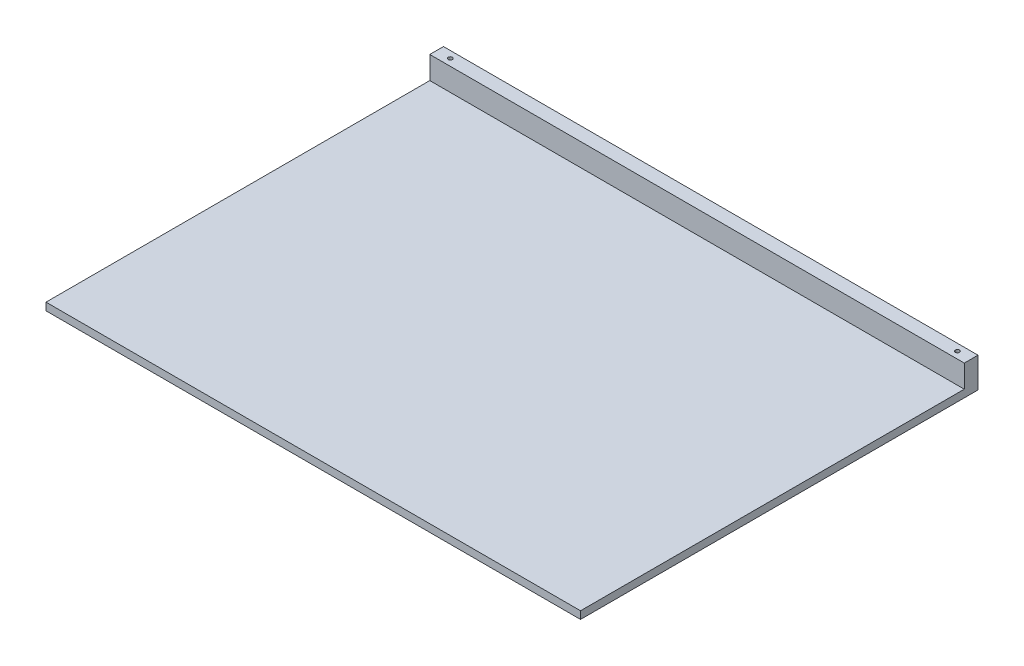
SolidWorks part; units mm, degrees
ref_plane "Alzado" through (0, 0, 0) normal (0, 0, 1) x (1, 0, 0)
ref_plane "Planta" through (0, 0, 0) normal (0, 1, 0) x (1, 0, 0)
ref_plane "Vista lateral" through (0, 0, 0) normal (1, 0, 0) x (0, 0, -1)
sketch "Croquis2" plane through (0, 0, 0) normal (0, 1, 0) x (1, 0, 0)
  line L1 (195, 145) -> (-195, 145)
  line L2 (195, 145) -> (195, -145)
  line L3 (195, -145) -> (-195, -145)
  line L4 (-195, 145) -> (-195, -145)
  line L5 (195, 145) -> (-195, -145) construction
  line L6 (195, -145) -> (-195, 145) construction
  point P0 (0, 0)
extrude "Saliente-Extruir2" add sketch "Croquis2" along normal blind 10
sketch "Croquis3" plane through (0, 10, 0) normal (0, 1, 0) x (1, 0, 0)
  line L0 (195, -145) -> (195, 145) construction
  line L1 (-195, -145) -> (195, -145)
  line L2 (-195, -145) -> (-195, -138)
  line L3 (-195, -138) -> (195, -138)
  line L4 (195, -145) -> (195, -138)
extrude "Saliente-Extruir3" add sketch "Croquis3" along normal blind 25
sketch "Croquis5" plane through (-195, 0, 0) normal (-1, 0, 0) x (0, 0, 1)
  line L0 (145, 0) -> (51.1207, -135.6896)
  line L2 (51.1207, -135.6896) -> (-145, 0)
  line L3 (-145, 0) -> (145, 0)
  dimension "D1" = 165
  dimension "D2" = 90
extrude "Saliente-Extruir4" add sketch "Croquis5" against normal blind 390
sketch "Croquis6" plane through (-195, 0, 0) normal (-1, 0, 0) x (0, 0, 1)
  line L0 (-145, 0) -> (145, 0)
  line L1 (145, 0) -> (51.1207, -135.6896)
  line L2 (51.1207, -135.6896) -> (-145, 0)
extrude "Cortar-Extruir1" cut sketch "Croquis6" against normal blind 180
sketch "Croquis7" plane through (195, 0, 0) normal (1, 0, 0) x (0, 0, -1)
  line L0 (145, 0) -> (-145, 0)
  line L1 (-145, 0) -> (-51.1207, -135.6896)
  line L2 (-51.1207, -135.6896) -> (145, 0)
extrude "Cortar-Extruir2" cut sketch "Croquis7" against normal blind 180
sketch "Croquis8" plane through (0, -67.8448, -46.9397) normal (0, -0.8224, -0.569) x (-1, 0, 0)
  line L0 (15, -119.2424) -> (105, 119.2424)
  line L1 (15, 119.2424) -> (195, 119.2424) construction
  line L2 (105, 119.2424) -> (75, 119.2424)
  line L3 (75, 119.2424) -> (15, -39.7475)
  line L4 (15, 119.2424) -> (15, -119.2424) construction
  line L5 (15, -39.7475) -> (15, -119.2424)
extrude "Saliente-Extruir5" add sketch "Croquis8" against normal blind 179
sketch "Croquis10" plane through (-195, 0, 0) normal (-1, 0, 0) x (0, 0, 1)
  line L0 (138, 35) -> (138, 10) construction
  line L1 (-145, 10) -> (138, 10)
  line L2 (-145, 10) -> (-145, 204.11)
  line L3 (-145, 204.11) -> (138, 204.11)
  line L4 (138, 10) -> (138, 204.11)
  dimension "D1" = 0
extrude "Cortar-Extruir5" cut sketch "Croquis10" against normal blind 236
sketch "Croquis11" plane through (-195, 0, 0) normal (-1, 0, 0) x (0, 0, 1)
  line L0 (145, 17.0241) -> (145, 0)
  line L1 (145, 0) -> (165.7896, 1.6032)
  line L2 (165.7896, 1.6032) -> (161.3582, 19.3089)
  line L3 (161.3582, 19.3089) -> (145, 17.0241)
extrude "Cortar-Extruir6" cut sketch "Croquis11" against normal blind 236
sketch "Croquis12" plane through (0, -67.8448, -46.9397) normal (0, -0.8224, -0.569) x (-1, 0, 0)
  line L0 (-15, -119.2424) -> (-105, 119.2424)
  line L1 (-195, 119.2424) -> (-15, 119.2424) construction
  line L2 (-105, 119.2424) -> (-75, 119.2424)
  line L3 (-75, 119.2424) -> (-15, -39.7475)
  line L4 (-15, -119.2424) -> (-15, 119.2424) construction
  line L5 (-15, -39.7475) -> (-15, -119.2424)
extrude "Saliente-Extruir6" add sketch "Croquis12" against normal blind 236
sketch "Croquis13" plane through (195, 0, 0) normal (1, 0, 0) x (0, 0, -1)
  line L1 (-138, 10) -> (201.7989, 10)
  line L2 (-138, 10) -> (-138, 246.8197)
  line L3 (-138, 246.8197) -> (201.7989, 246.8197)
  line L4 (201.7989, 10) -> (201.7989, 246.8197)
  line L5 (-145, 0) -> (-189.7765, 0)
  line L6 (-145, 0) -> (-145, 75.1047)
  line L7 (-145, 75.1047) -> (-189.7765, 75.1047)
  line L8 (-189.7765, 0) -> (-189.7765, 75.1047)
extrude "Cortar-Extruir7" cut sketch "Croquis13" against normal blind 500
sketch "Croquis14" plane through (195, 0, 0) normal (1, 0, 0) x (0, 0, -1)
  line L1 (-138, 35) -> (-197.446, 35)
  line L2 (-138, 35) -> (-138, 116.4359)
  line L3 (-138, 116.4359) -> (-197.446, 116.4359)
  line L4 (-197.446, 35) -> (-197.446, 116.4359)
extrude "Cortar-Extruir8" cut sketch "Croquis14" against normal blind 500
sketch "Croquis15" plane through (-195, 0, 0) normal (-1, 0, 0) x (0, 0, 1)
  line L0 (-145, 0) -> (145, 0) construction
  line L1 (-127, 0) -> (-77, 0)
  line L2 (-127, 0) -> (-127, -5)
  line L3 (-127, -5) -> (-77, -5)
  line L4 (-77, 0) -> (-77, -5)
  line L6 (138, 35) -> (138, 10) construction
  dimension "D1" = 50
  dimension "D2" = 215
  dimension "D3" = 5
extrude "Cortar-Extruir9" cut sketch "Croquis15" against normal blind 500
sketch "Croquis16" plane through (0, 10, 0) normal (0, 1, 0) x (1, 0, 0)
  line L1 (-195, 145) -> (195, 145)
  line L2 (-195, 145) -> (-195, -138)
  line L3 (-195, -138) -> (195, -138)
  line L4 (195, 145) -> (195, -138)
extrude "Cortar-Extruir10" cut sketch "Croquis16" against normal blind 10
sketch "Croquis17" plane through (0, 0, 0) normal (0, 1, 0) x (1, 0, 0)
  line L0 (-99.4138, 127) -> (-99.4138, 145) construction
  line L1 (-105, 145) -> (-75, 145) construction
  line L2 (-75, 145) -> (-75, 127) construction
  line L3 (-69.4138, 127) -> (-99.4138, 127) construction
  line L5 (15, 145) -> (-15, 145) construction
  line L6 (75, 145) -> (105, 145) construction
  circle A0 centre (-87.205, 136) radius 3.75
  circle A1 centre (0, 136) radius 3.75
  circle A2 centre (87.205, 136) radius 3.75
  dimension "D1" = 9
  dimension "D2" = 7.5
  dimension "D7" = 7.5
  dimension "D8" = 7.5
  dimension "D3" = 9
  dimension "D4" = 12.205
  dimension "D5" = 12.205
  dimension "D6" = 9
extrude "Cortar-Extruir11" cut sketch "Croquis17" against normal blind 10
sketch "Croquis18" plane through (0, 0, 0) normal (0, 1, 0) x (1, 0, 0)
  circle A0 centre (-87.205, 136) radius 1.5
  circle A1 centre (-87.205, 136) radius 3.75
  circle A2 centre (0, 136) radius 3.75
  circle A3 centre (0, 136) radius 1.5
  circle A4 centre (87.205, 136) radius 1.5
  circle A5 centre (87.205, 136) radius 3.75
extrude "Saliente-Extruir8" add sketch "Croquis18" against normal blind 4
sketch "Croquis19" plane through (0, 0, 0) normal (0, 1, 0) x (1, 0, 0)
  line L0 (-15, -48.3333) -> (-53.8966, 77) construction
  line L1 (53.8966, 77) -> (15, -48.3333) construction
  line L2 (-17.1724, -138) -> (17.1724, -138) construction
  circle A0 centre (-52.5333, 22) radius 1.5
  circle A1 centre (0, 22) radius 1.5
  circle A2 centre (52.5333, 22) radius 1.5
  circle A3 centre (0, -58) radius 1.5
  circle A4 centre (0, -116) radius 1.5
  dimension "D1" = 15
  dimension "D2" = 15
  dimension "D6" = 80
  dimension "D7" = 3
  dimension "D3" = 160
  dimension "D4" = 0
  dimension "D5" = 0
  dimension "D8" = 22
extrude "Saliente-Extruir10" add sketch "Croquis19" along normal blind 15
sketch "Croquis20" plane through (0, 0, 0) normal (0, 1, 0) x (1, 0, 0)
  circle A0 centre (-87.205, 136) radius 1.5
  circle A1 centre (0, 136) radius 1.5
  circle A2 centre (87.205, 136) radius 1.5
extrude "Saliente-Extruir11" add sketch "Croquis20" along normal blind 15 separate body
sketch "Croquis21" plane through (0, 0, 0) normal (0, 1, 0) x (1, 0, 0)
  line L1 (-195, -138) -> (195, -138)
  line L2 (-195, -138) -> (-195, 145)
  line L3 (-195, 145) -> (195, 145)
  line L4 (195, -138) -> (195, 145)
extrude "Saliente-Extruir12" add sketch "Croquis21" along normal blind 10
sketch "Croquis22" plane through (0, 15, 0) normal (0, 1, 0) x (1, 0, 0)
  circle A0 centre (0, -116) radius 1.5
  circle A1 centre (0, -58) radius 1.5
  circle A2 centre (-52.5333, 22) radius 1.5
  circle A3 centre (0, 22) radius 1.5
  circle A4 centre (52.5333, 22) radius 1.5
  circle A5 centre (87.205, 136) radius 1.5
  circle A6 centre (0, 136) radius 1.5
  circle A7 centre (-87.205, 136) radius 1.5
extrude "Cortar-Extruir12" cut sketch "Croquis22" against normal blind 47
sketch "Croquis26" plane through (-195, 0, 0) normal (-1, 0, 0) x (0, 0, 1)
  line L1 (-145, 10) -> (138, 10)
  line L2 (-145, 10) -> (-145, 5.5)
  line L3 (-145, 5.5) -> (138, 5.5)
  line L4 (138, 10) -> (138, 5.5)
extrude "Cortar-Extruir16" cut sketch "Croquis26" against normal blind 500
sketch "Croquis27" plane through (-195, 0, 0) normal (-1, 0, 0) x (0, 0, 1)
  line L0 (145, 35) -> (145, 0) construction
  line L1 (138, 35) -> (145, 35)
  line L2 (138, 35) -> (138, 25.5)
  line L3 (138, 25.5) -> (145, 25.5)
  line L4 (145, 35) -> (145, 25.5)
  line L5 (-145, 5.5) -> (138, 5.5) construction
  dimension "D1" = 20
extrude "Cortar-Extruir17" cut sketch "Croquis27" against normal blind 500
sketch "Croquis28" plane through (-195, 0, 0) normal (-1, 0, 0) x (0, 0, 1)
  line L0 (51.1207, -135.6896) -> (80.7069, -92.9268)
  line L1 (51.1207, -135.6896) -> (19.4598, -113.7845)
  line L2 (80.7069, -92.9268) -> (49.046, -71.0217)
  line L3 (19.4598, -113.7845) -> (49.046, -71.0217)
  line L4 (51.1207, -135.6896) -> (145, 0) construction
  dimension "D1" = 113
  dimension "D2" = 38.5
extrude "Cortar-Extruir18" cut sketch "Croquis28" against normal blind 500
sketch "Croquis29" plane through (0, -25.082, -17.3534) normal (0, -0.8224, -0.569) x (-1, 0, 0)
  line L0 (-15, -119.2424) -> (15, -119.2424) construction
  circle A0 centre (0, -91.2424) radius 3.5
  dimension "D1" = 28
extrude "Cortar-Extruir19" cut sketch "Croquis29" against normal blind 20
sketch "Croquis31" plane through (195, 0, 0) normal (1, 0, 0) x (0, 0, -1)
  line L0 (-71.4506, -70.7146) -> (-76.0024, -64.1357)
  line L1 (-71.4506, -70.7146) -> (-58.704, -61.8956)
  line L2 (-76.0024, -64.1357) -> (-63.2558, -55.3167)
  line L3 (-58.704, -61.8956) -> (-63.2558, -55.3167)
  line L6 (-49.046, -71.0217) -> (-80.7069, -92.9268) construction
  line L7 (-145, 0) -> (-80.7069, -92.9268) construction
  point P4 (-69.6291, -59.7262)
  dimension "D1" = 13
  dimension "D2" = 8
  dimension "D3" = 15.5
  dimension "D4" = 28
extrude "Cortar-Extruir20" cut sketch "Croquis31" against normal blind 314
sketch "Croquis32" plane through (0, -67.8448, 98.0603) normal (0, -0.569, 0.8224) x (1, 0, 0)
  line L0 (-15, 82.5) -> (15, 82.5) construction
  circle A0 centre (0, 47.5) radius 3.5
  dimension "D1" = 35
extrude "Cortar-Extruir21" cut sketch "Croquis32" against normal blind 25
sketch "Croquis33" plane through (195, 0, 0) normal (1, 0, 0) x (0, 0, -1)
  line L1 (-145, 0) -> (163.8337, 0)
  line L2 (-145, 0) -> (-145, 37.0388)
  line L3 (-145, 37.0388) -> (163.8337, 37.0388)
  line L4 (163.8337, 0) -> (163.8337, 37.0388)
extrude "Cortar-Extruir22" cut sketch "Croquis33" against normal blind 500
sketch "Croquis34" plane through (0, 0, 0) normal (0, 1, 0) x (1, 0, 0)
  line L1 (-195, 145) -> (195, 145)
  line L2 (-195, 145) -> (-195, -145)
  line L3 (-195, -145) -> (195, -145)
  line L4 (195, 145) -> (195, -145)
  line L5 (-195, 145) -> (195, -145) construction
  line L6 (-195, -145) -> (195, 145) construction
  circle A0 centre (0, -58) radius 1.5
  circle A1 centre (0, -116) radius 1.5
  circle A2 centre (-52.5333, 22) radius 1.5
  circle A3 centre (0, 22) radius 1.5
  circle A4 centre (52.5333, 22) radius 1.5
  circle A5 centre (-87.205, 136) radius 1.5
  circle A6 centre (0, 136) radius 1.5
  circle A7 centre (87.205, 136) radius 1.5
  point P0 (0, 0)
extrude "Saliente-Extruir14" add sketch "Croquis34" along normal blind 5.5
sketch "Croquis35" plane through (0, 5.5, 0) normal (0, 1, 0) x (1, 0, 0)
  line L1 (-195, -145) -> (195, -145)
  line L2 (-195, -145) -> (-195, -135)
  line L3 (-195, -135) -> (195, -135)
  line L4 (195, -145) -> (195, -135)
extrude "Saliente-Extruir15" add sketch "Croquis35" along normal blind 22
sketch "Croquis36" plane through (-195, 0, 0) normal (-1, 0, 0) x (0, 0, 1)
  line L0 (-123.3196, -5) -> (-123.3196, -15)
  line L1 (-127, -5) -> (-77, -5) construction
  line L2 (19.4598, -113.7845) -> (-145, 0) construction
  line L3 (-123.3196, -15) -> (49.046, -71.0217)
  line L4 (49.046, -71.0217) -> (19.4598, -113.7845)
  line L5 (19.4598, -113.7845) -> (-123.3196, -15)
  dimension "D1" = 10
extrude "Cortar-Extruir23" cut sketch "Croquis36" against normal blind 488 contours L5 L4 L3
sketch "Croquis37" plane through (-195, 0, 0) normal (-1, 0, 0) x (0, 0, 1)
  line L3 (-115.7721, -5) -> (-115.7721, -17.453) construction
  line L4 (-127, -5) -> (-77, -5) construction
  line L5 (-123.3196, -15) -> (49.046, -71.0217) construction
  line L6 (-115.7721, -17.453) -> (39.046, -17.453)
  line L7 (49.046, -71.0217) -> (49.046, -27.453)
  line L8 (-115.7721, -17.453) -> (49.046, -71.0217)
  arc A1 (49.046, -27.453) -> (39.046, -17.453) centre (39.046, -27.453) ccw
  dimension "D1" = 12.453
  dimension "D3" = 90
  dimension "D4" = 90
extrude "Cortar-Extruir28" cut sketch "Croquis37" against normal blind 479.5
sketch "Croquis38" plane through (0, -67.8448, 98.0603) normal (0, -0.569, 0.8224) x (1, 0, 0)
  circle A0 centre (0, 44.5) radius 3.5
  circle A1 centre (0, 47.5) radius 3.5 construction
  dimension "D1" = 3
extrude "Cortar-Extruir29" cut sketch "Croquis38" against normal blind 25
sketch "Croquis39" plane through (0, -32, 0) normal (0, 1, 0) x (1, 0, 0)
  circle A0 centre (0, -116) radius 1.5
extrude "Saliente-Extruir16" add sketch "Croquis39" along normal blind 9
sketch "Croquis40" plane through (0, -67.8448, 98.0603) normal (0, -0.569, 0.8224) x (1, 0, 0)
  circle A0 centre (0, 47.5) radius 3.5
extrude "Saliente-Extruir17" add sketch "Croquis40" against normal blind 25
sketch "Croquis41" plane through (0, -67.8448, 98.0603) normal (0, -0.569, 0.8224) x (1, 0, 0)
  circle A0 centre (0, 44.5) radius 3.5
extrude "Cortar-Extruir30" cut sketch "Croquis41" against normal blind 25
sketch "Croquis43" plane through (-195, 0, 0) normal (-1, 0, 0) x (0, 0, 1)
  line L1 (-145, 0) -> (162.1283, 0)
  line L2 (-145, 0) -> (-145, -102.2321)
  line L3 (-145, -102.2321) -> (162.1283, -102.2321)
  line L4 (162.1283, 0) -> (162.1283, -102.2321)
extrude "Cortar-Extruir32" cut sketch "Croquis43" against normal blind 500
sketch "Croquis44" plane through (0, 27.5, 0) normal (0, 1, 0) x (1, 0, 0)
  line L0 (195, -145) -> (195, -135) construction
  line L1 (-195, -135) -> (-195, -145) construction
  line L2 (195, -135) -> (-195, -135) construction
  circle A0 centre (-185, -140) radius 1.5
  circle A1 centre (185, -140) radius 1.5
  dimension "D1" = 10
  dimension "D2" = 10
  dimension "D3" = 5
  dimension "D4" = 5
extrude "Cortar-Extruir34" cut sketch "Croquis44" against normal blind 50
sketch "Croquis45" plane through (0, 5.5, 0) normal (0, 1, 0) x (1, 0, 0)
  line L1 (-195, 145) -> (195, 145)
  line L2 (-195, 145) -> (-195, -145)
  line L3 (-195, -145) -> (195, -145)
  line L4 (195, 145) -> (195, -145)
extrude "Cortar-Extruir37" cut sketch "Croquis45" along normal blind 50
sketch "Croquis46" plane through (0, 5.5, 0) normal (0, 1, 0) x (1, 0, 0)
  line L0 (195, -145) -> (195, 145) construction
  line L1 (-195, -145) -> (195, -145)
  line L2 (-195, -145) -> (-195, -135)
  line L3 (-195, -135) -> (195, -135)
  line L4 (195, -145) -> (195, -135)
  circle A0 centre (-185, -140) radius 1.5
  circle A1 centre (185, -140) radius 1.5
extrude "Saliente-Extruir19" add sketch "Croquis46" along normal blind 16.5
sketch "Croquis48" plane through (0, 5.5, 0) normal (0, 1, 0) x (1, 0, 0)
  line L1 (-195, 145) -> (195, 145)
  line L2 (-195, 145) -> (-195, -135)
  line L3 (-195, -135) -> (195, -135)
  line L4 (195, 145) -> (195, -135)
extrude "Cortar-Extruir38" cut sketch "Croquis48" against normal blind 16.5
sketch "Croquis49" plane through (0, 0, 0) normal (0, -1, 0) x (-1, 0, 0)
  line L1 (195, -145) -> (-195, -145)
  line L2 (195, -145) -> (195, -425)
  line L3 (195, -425) -> (-195, -425)
  line L4 (-195, -145) -> (-195, -425)
extrude "Saliente-Extruir20" add sketch "Croquis49" against normal blind 5.5
